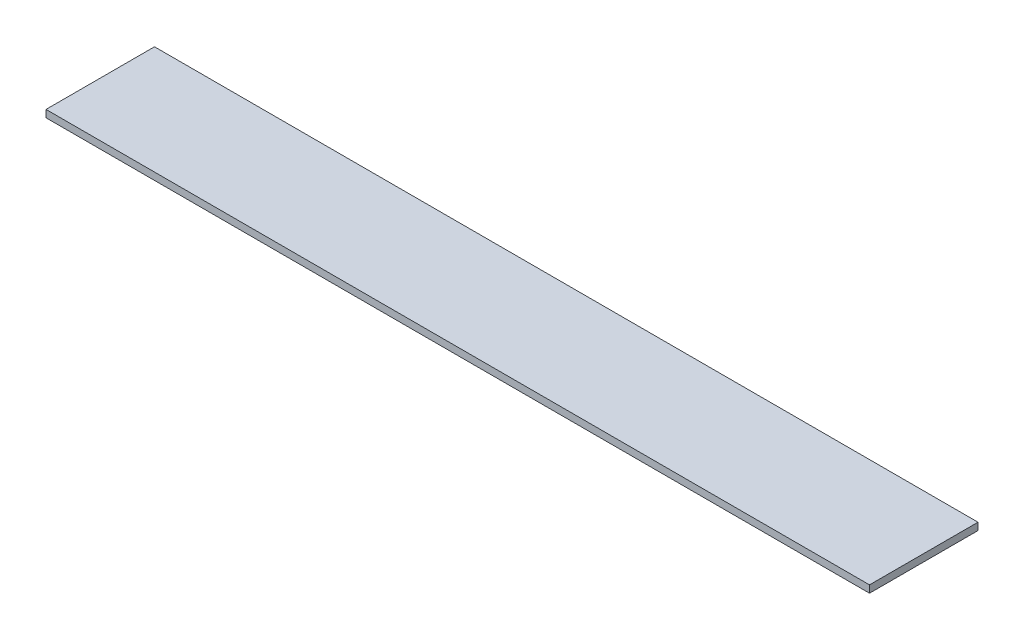
SolidWorks part; units mm, degrees
ref_plane "Front Plane" through (0, 0, 0) normal (0, 0, 1) x (1, 0, 0)
ref_plane "Top Plane" through (0, 0, 0) normal (0, 1, 0) x (1, 0, 0)
ref_plane "Right Plane" through (0, 0, 0) normal (1, 0, 0) x (0, 0, -1)
sketch "Sketch2" plane through (0, 0, 0) normal (0, 1, 0) x (1, 0, 0)
  line L1 (0, 0) -> (539.75, 0)
  line L2 (0, 0) -> (0, 71.12)
  line L3 (0, 71.12) -> (539.75, 71.12)
  line L4 (539.75, 0) -> (539.75, 71.12)
  dimension "D1" = 71.12
  dimension "D2" = 539.75
extrude "Boss-Extrude1" add sketch "Sketch2" along normal blind 4.7625
